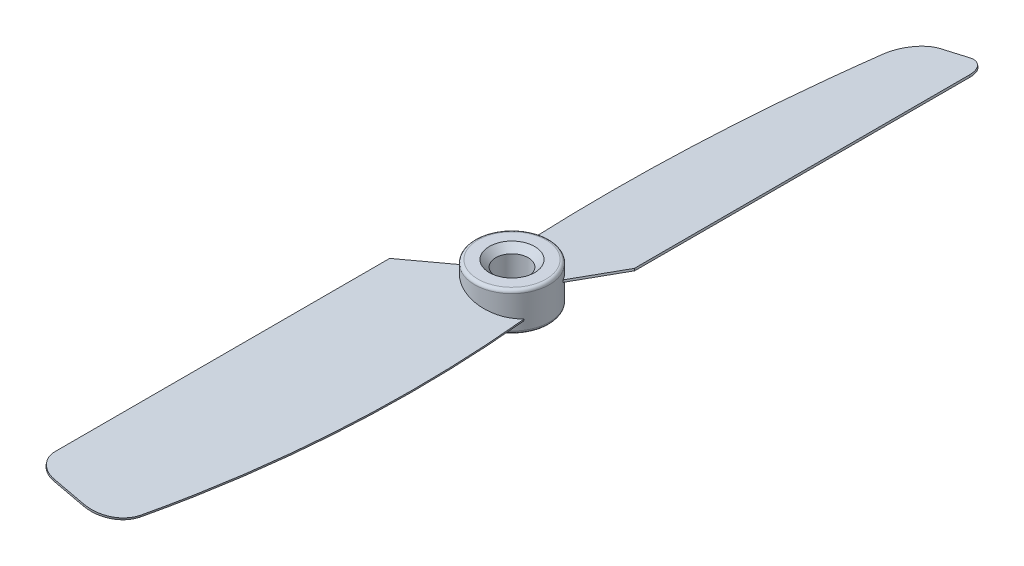
SolidWorks part; units mm, degrees
material "Thornel VCB-20 Carbon Cloth"
ref_plane "Front Plane" through (0, 0, 0) normal (0, 0, 1) x (1, 0, 0)
ref_plane "Top Plane" through (0, 0, 0) normal (0, 1, 0) x (1, 0, 0)
ref_plane "Right Plane" through (0, 0, 0) normal (1, 0, 0) x (0, 0, -1)
sketch "Sketch1" plane through (0, 0, 0) normal (0, 1, 0) x (1, 0, 0)
  circle A0 centre (0, 0) radius 5.75
  dimension "D1" = 11.5
extrude "Boss-Extrude2" add sketch "Sketch1" along normal mid plane 6
sketch "Sketch2" plane through (0, 0, 0) normal (0, 0, 1) x (1, 0, 0)
  line L0 (-5.75, 1.3275) -> (5.75, -1.3275) construction
  line L1 (-5.75, 3) -> (-5.75, -3) construction
  line L2 (5.75, -3) -> (5.75, 3) construction
  line L3 (-5.75, -3) -> (5.75, -3) construction
  dimension "D1" = 13
ref_plane "Plane1" through (0, 0, 0) normal (-0.225, -0.9744, 0) x (0.9744, -0.225, 0)
sketch "Sketch4" plane through (0, 0, 0) normal (-0.225, -0.9744, 0) x (0.9744, -0.225, 0)
  line L1 (-10.4096, 8.775) -> (-10.4096, 60.5)
  line L2 (-7.4096, 63.5) -> (-2.7095, 63.5)
  line L3 (-10.4096, 8.775) -> (-4.9833, 2.7672)
  arc A1 (2.1884, 59.5054) -> (-2.7095, 63.5) centre (-2.7095, 58.5) ccw
  arc A2 (-10.4096, 60.5) -> (-7.4096, 63.5) centre (-7.4096, 60.5) cw
  arc A3 (4.9833, 2.7672) -> (-4.9833, 2.7672) centre (0, 0) ccw
  spline S0 degree 2 poles (4.9833, 2.7672) (7.3686, 31.4454) (2.1884, 59.5054) knots 0 0 0 1 1 1
  dimension "D1" = 11.4
  dimension "D3" = 5
  dimension "D4" = 3
extrude "Boss-Extrude10" add sketch "Sketch4" along normal mid plane 0.3
pattern_circular "CirPattern1" count 2 over 360 about axis through (0, 3, 0) along (0, -1, 0) of "Boss-Extrude10"
sketch "Sketch5" plane through (0, -3, 0) normal (0, -1, 0) x (1, 0, 0)
  circle A0 centre (0, 0) radius 2.5
  dimension "D1" = 5
extrude "Cut-Extrude1" cut sketch "Sketch5" against normal through all
fillet "Fillet1" radius 0.5 2 edges at (0, 3, 5.75) (0, -3, 5.75)
chamfer "Chamfer1" distance 1 angle 45 2 edges at (0, -3, -2.5) (0, 3, -2.5)
